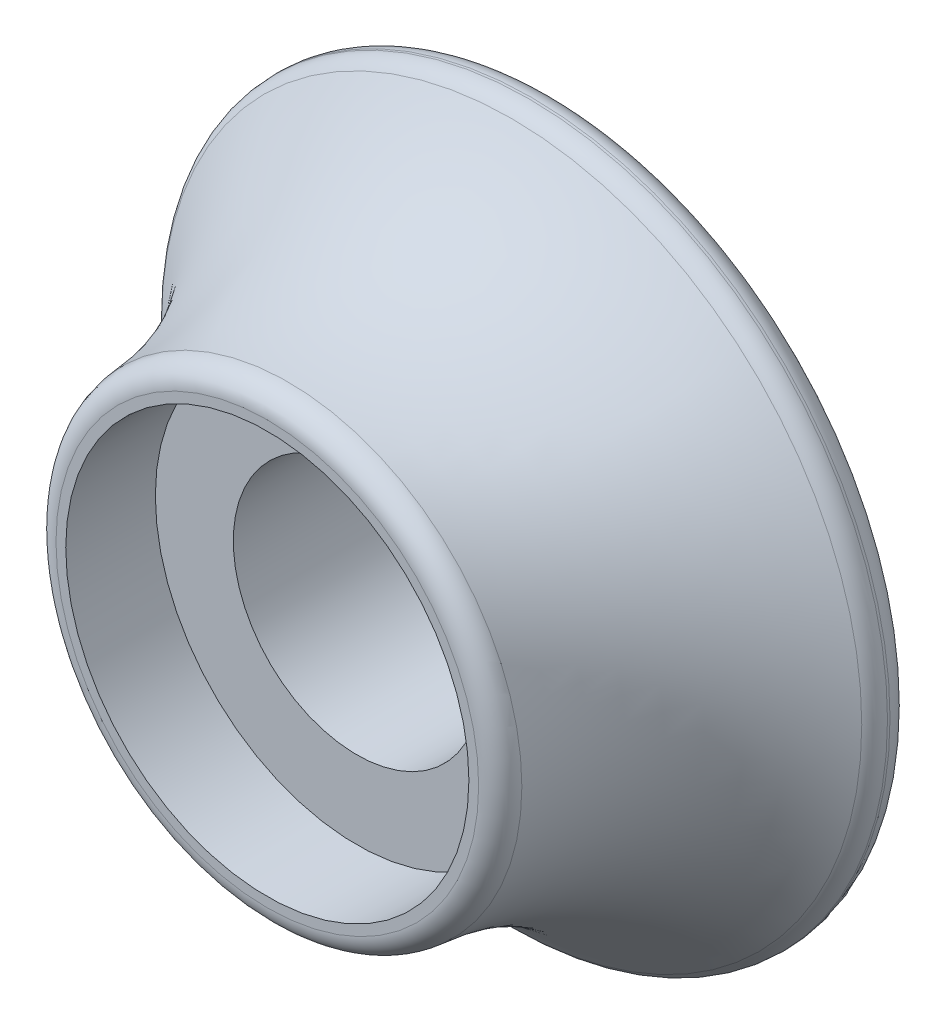
SolidWorks part; units mm, degrees
material "PET"
ref_plane "Front Plane" through (0, 0, 0) normal (0, 0, 1) x (1, 0, 0)
ref_plane "Top Plane" through (0, 0, 0) normal (0, 1, 0) x (1, 0, 0)
ref_plane "Right Plane" through (0, 0, 0) normal (1, 0, 0) x (0, 0, -1)
sketch "Sketch1" plane through (0, 0, 0) normal (0, 0, 1) x (1, 0, 0)
  circle A0 centre (0, 0) radius 25.4
  dimension "D1" = 50.8
extrude "Boss-Extrude1" add sketch "Sketch1" along normal blind 20.32
sketch "Sketch2" plane through (0, 0, 20.32) normal (0, 0, 1) x (1, 0, 0)
  circle A0 centre (0, 0) radius 14.2875
  dimension "D1" = 28.575
extrude "Cut-Extrude1" cut sketch "Sketch2" against normal blind 6.35
sketch "Sketch3" plane through (0, 0, 20.32) normal (0, 0, 1) x (1, 0, 0)
  circle A0 centre (0, 0) radius 16.51
  circle A1 centre (0, 0) radius 14.2875 construction
  circle A3 centre (0, 0) radius 25.4
  dimension "D1" = 2.2225
  dimension "D2" = 50.8
extrude "Cut-Extrude2" cut sketch "Sketch3" against normal blind 17.78
sketch "Sketch5" plane through (0, 0, 0) normal (0, 1, 0) x (1, 0, 0)
  line L0 (-25.4, -2.54) -> (-16.51, -2.54)
  line L1 (-16.51, -2.54) -> (-16.51, -20.32)
  line L2 (0, 0) -> (0, 8.1056) construction
  arc A0 (-25.4, -2.54) -> (-16.51, -20.32) centre (-38.8619, -20.3835) cw
  dimension "D1" = 22.352
revolve "Revolve1" add sketch "Sketch5" angle 360 about L2
sketch "Sketch6" plane through (0, 0, 13.97) normal (0, 0, 1) x (1, 0, 0)
  circle A0 centre (0, 0) radius 8.763
  dimension "D1" = 17.526
extrude "Cut-Extrude3" cut sketch "Sketch6" against normal through all
fillet "Fillet1" radius 1.5875 3 edges at (16.51, 0, 20.32) (25.4, 0, 2.54) (25.4, 0, 0)
